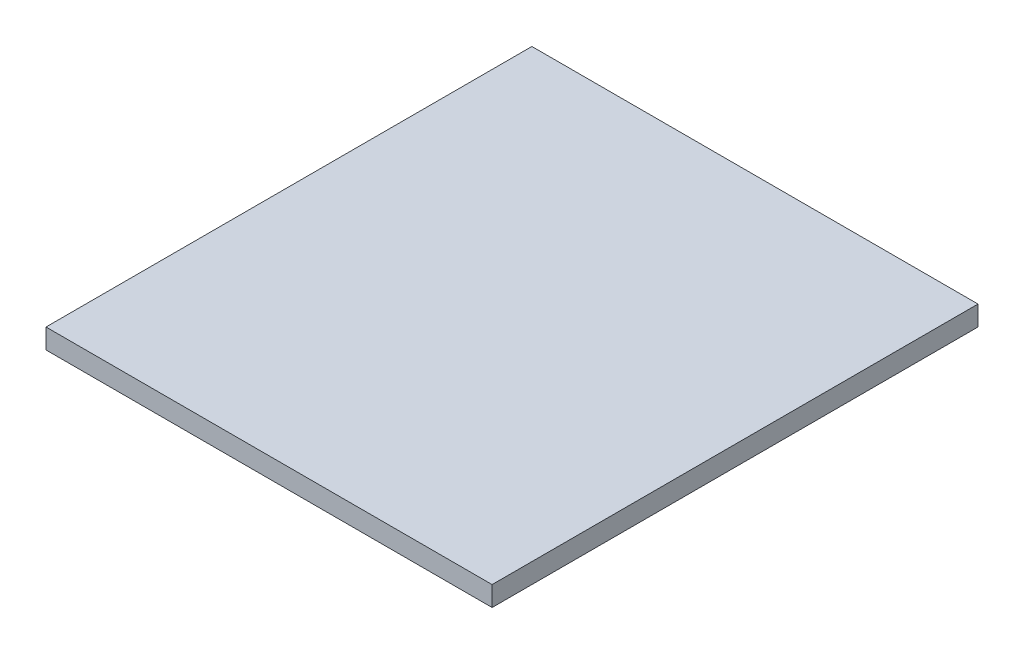
SolidWorks part; units mm, degrees
ref_plane "Front Plane" through (0, 0, 0) normal (0, 0, 1) x (1, 0, 0)
ref_plane "Top Plane" through (0, 0, 0) normal (0, 1, 0) x (1, 0, 0)
ref_plane "Right Plane" through (0, 0, 0) normal (1, 0, 0) x (0, 0, -1)
sketch "Sketch1" plane through (0, 0, 0) normal (0, 0, 1) x (1, 0, 0)
  line L0 (289.8, 17.5) -> (289.8, -12.5) construction
  line L1 (5, -12.5) -> (289.8, -12.5)
  line L2 (5, -12.5) -> (5, 0.2)
  line L3 (5, 0.2) -> (289.8, 0.2)
  line L4 (289.8, -12.5) -> (289.8, 0.2)
  dimension "D1" = 12.7
extrude "Boss-Extrude1" add sketch "Sketch1" along normal up to surface (310.2 mm away)
